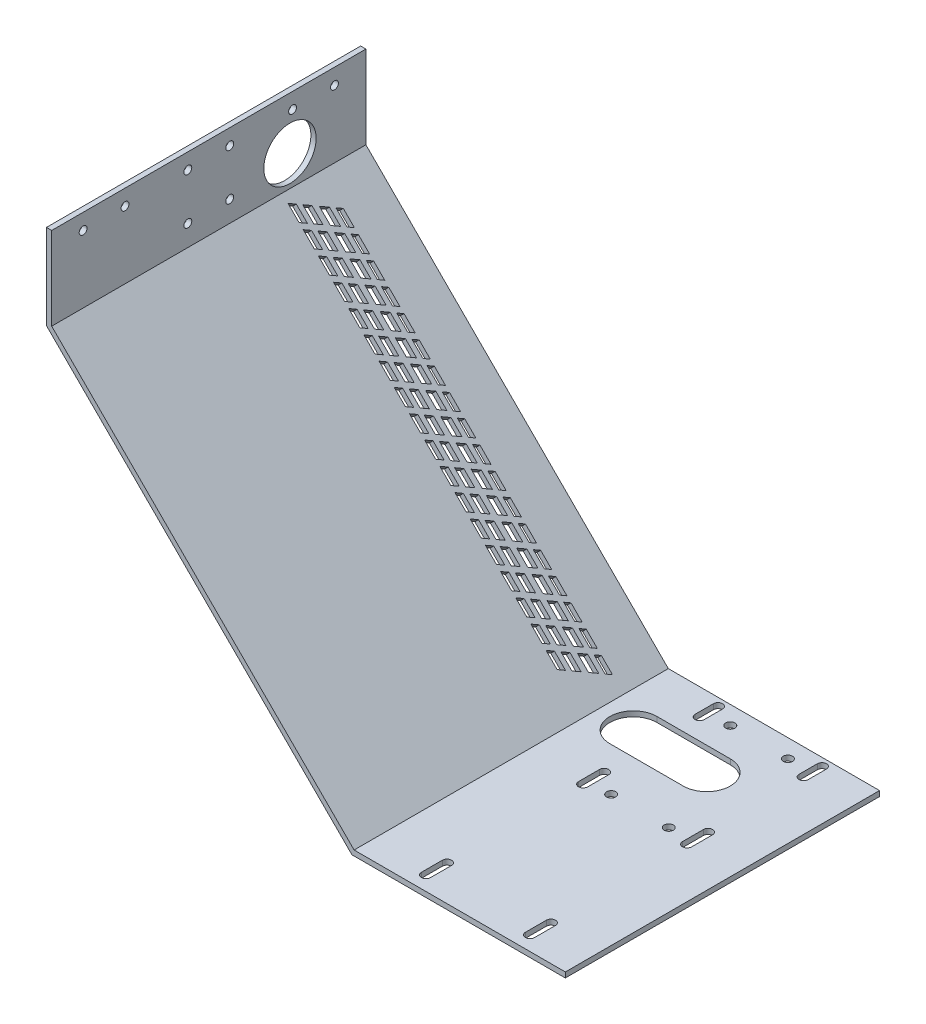
SolidWorks part; units mm, degrees
ref_plane "前视基准面" through (0, 0, 0) normal (0, 0, 1) x (1, 0, 0)
ref_plane "上视基准面" through (0, 0, 0) normal (0, 1, 0) x (1, 0, 0)
ref_plane "右视基准面" through (0, 0, 0) normal (1, 0, 0) x (0, 0, -1)
other "Configuration Table"
ref_plane "基准面1" through (0, 0, 0) normal (0, 0, -1) x (-1, 0, 0)
sketch "草图1" plane through (0, 0, 0) normal (0, 0, -1) x (-1, 0, 0)
  line L0 (199.1726, -50) -> (1, -50)
  line L1 (1, -50) -> (1, -199.1726)
  line L2 (1, -199.1726) -> (82.5, -199.1726)
  line L3 (82.5, -199.1726) -> (199.1726, -82.5)
  line L4 (199.1726, -82.5) -> (199.1726, -50)
  dimension "D1" = 81.5
  dimension "D2" = 198.1726
  dimension "D3" = 116.6726
  dimension "D4" = 149.1726
extrude "凸台-拉伸1" add sketch "草图1" against normal blind 120
sketch "草图2" plane through (0, 0, 120) normal (0, 0, 1) x (1, 0, 0)
  line L0 (-197.1726, -50) -> (-197.1726, -81.6716)
  line L1 (-197.1726, -81.6716) -> (-81.6716, -197.1726)
  line L2 (-81.6716, -197.1726) -> (-1, -197.1726)
  line L3 (-1, -197.1726) -> (-1, -50)
  line L4 (-1, -50) -> (-197.1726, -50)
  line L5 (-199.1726, -82.5) -> (-199.1726, -50) construction
  line L6 (-1, -199.1726) -> (-82.5, -199.1726) construction
  dimension "D1" = 2
  dimension "D2" = 117.501
  dimension "D3" = 198.1726
  dimension "D4" = 2
  dimension "D5" = 117.501
  dimension "D6" = 149.1726
extrude "切除-拉伸1" cut sketch "草图2" against normal through all
sketch "草图3" plane through (0, -199.1726, 0) normal (0, -1, 0) x (1, 0, 0)
  line L0 (-57.95, 106.5) -> (-57.95, 114.5)
  line L1 (-61.45, 114.5) -> (-61.45, 106.5)
  line L2 (-1, 120) -> (-1, 0) construction
  line L3 (-1, 0) -> (-82.5, 0) construction
  arc A0 (-61.45, 106.5) -> (-57.95, 106.5) centre (-59.7, 106.5) ccw
  arc A1 (-57.95, 114.5) -> (-61.45, 114.5) centre (-59.7, 114.5) ccw
  dimension "D1" = 1.75
  dimension "D2" = 58.7
  dimension "D3" = 106.5
  dimension "D4" = 114.5
extrude "切除-拉伸2" cut sketch "草图3" against normal through all
sketch "草图4" plane through (0, -199.1726, 0) normal (0, -1, 0) x (1, 0, 0)
  line L0 (-18.25, 106.5) -> (-18.25, 114.5)
  line L1 (-21.75, 114.5) -> (-21.75, 106.5)
  line L2 (-61.45, 114.5) -> (-61.45, 106.5) construction
  arc A0 (-18.25, 114.5) -> (-21.75, 114.5) centre (-20, 114.5) ccw
  arc A1 (-21.75, 106.5) -> (-18.25, 106.5) centre (-20, 106.5) ccw
  dimension "D1" = 1.75
  dimension "D2" = 41.45
  dimension "D3" = 8
extrude "切除-拉伸3" cut sketch "草图4" against normal through all
sketch "草图5" plane through (0, -199.1726, 0) normal (0, -1, 0) x (1, 0, 0)
  line L0 (-61.45, 54.5) -> (-61.45, 46.5)
  line L1 (-57.95, 46.5) -> (-57.95, 54.5)
  line L2 (-61.45, 114.5) -> (-61.45, 106.5) construction
  arc A0 (-61.45, 46.5) -> (-57.95, 46.5) centre (-59.7, 46.5) ccw
  arc A1 (-57.95, 54.5) -> (-61.45, 54.5) centre (-59.7, 54.5) ccw
  dimension "D1" = 1.75
  dimension "D2" = 1.75
  dimension "D3" = 52
  dimension "D4" = 60
extrude "切除-拉伸4" cut sketch "草图5" against normal through all
sketch "草图6" plane through (0, -199.1726, 0) normal (0, -1, 0) x (1, 0, 0)
  line L0 (-21.75, 54.5) -> (-21.75, 46.5)
  line L1 (-18.25, 46.5) -> (-18.25, 54.5)
  line L2 (-61.45, 54.5) -> (-61.45, 46.5) construction
  arc A0 (-18.25, 54.5) -> (-21.75, 54.5) centre (-20, 54.5) ccw
  arc A1 (-21.75, 46.5) -> (-18.25, 46.5) centre (-20, 46.5) ccw
  dimension "D1" = 1.75
  dimension "D2" = 41.45
  dimension "D3" = 52
  dimension "D4" = 60
extrude "切除-拉伸5" cut sketch "草图6" against normal through all
sketch "草图7" plane through (0, -199.1726, 0) normal (0, -1, 0) x (1, 0, 0)
  line L0 (-61.45, 10) -> (-61.45, 3)
  line L1 (-57.95, 3) -> (-57.95, 10)
  line L2 (-61.45, 54.5) -> (-61.45, 46.5) construction
  arc A0 (-61.45, 3) -> (-57.95, 3) centre (-59.7, 3) ccw
  arc A1 (-57.95, 10) -> (-61.45, 10) centre (-59.7, 10) ccw
  dimension "D1" = 1.75
  dimension "D2" = 1.75
  dimension "D3" = 96.5
  dimension "D4" = 103.5
extrude "切除-拉伸6" cut sketch "草图7" against normal through all
sketch "草图8" plane through (0, -199.1726, 0) normal (0, -1, 0) x (1, 0, 0)
  line L0 (-18.25, 3) -> (-18.25, 10)
  line L1 (-21.75, 10) -> (-21.75, 3)
  line L2 (-61.45, 54.5) -> (-61.45, 46.5) construction
  arc A0 (-18.25, 10) -> (-21.75, 10) centre (-20, 10) ccw
  arc A1 (-21.75, 3) -> (-18.25, 3) centre (-20, 3) ccw
  dimension "D1" = 1.75
  dimension "D2" = 41.45
  dimension "D3" = 44.5
  dimension "D4" = 51.5
extrude "切除-拉伸7" cut sketch "草图8" against normal through all
sketch "草图9" plane through (-139.4221, -139.4221, 0) normal (0.7071, 0.7071, 0) x (-0.7071, 0.7071, 0)
  line L0 (-56.4528, 25.5) -> (-55.0094, 28)
  line L1 (-55.0094, 28) -> (-61.0094, 28)
  line L2 (-61.0094, 28) -> (-62.4528, 25.5)
  line L3 (-62.4528, 25.5) -> (-56.4528, 25.5)
  line L4 (-81.6716, 0) -> (-81.6716, 120) construction
  dimension "D1" = 19.2188
  dimension "D2" = 20.6622
  dimension "D3" = 25.2188
  dimension "D4" = 26.6622
  dimension "D5" = 25.5
  dimension "D6" = 28
extrude "切除-拉伸8" cut sketch "草图9" against normal through all
sketch "草图10" plane through (-139.4221, -139.4221, 0) normal (0.7071, 0.7071, 0) x (-0.7071, 0.7071, 0)
  line L0 (-59.2056, 20.7321) -> (-57.6075, 23.5)
  line L1 (-57.6075, 23.5) -> (-63.6075, 23.5)
  line L2 (-63.6075, 23.5) -> (-65.2056, 20.7321)
  line L3 (-65.2056, 20.7321) -> (-59.2056, 20.7321)
  dimension "D1" = 2.5981
  dimension "D2" = 4.1962
  dimension "D3" = 8.5981
  dimension "D4" = 10.1962
  dimension "D5" = 2
  dimension "D6" = 4.7679
extrude "切除-拉伸9" cut sketch "草图10" against normal through all
sketch "草图11" plane through (-139.4221, -139.4221, 0) normal (0.7071, 0.7071, 0) x (-0.7071, 0.7071, 0)
  line L0 (-50.5, 32) -> (-51.8094, 29.7321)
  line L1 (-51.8094, 29.7321) -> (-45.8094, 29.7321)
  line L2 (-45.8094, 29.7321) -> (-44.5, 32)
  line L3 (-44.5, 32) -> (-50.5, 32)
  dimension "D1" = 13.3962
  dimension "D2" = 14.7056
  dimension "D3" = 19.3962
  dimension "D4" = 20.7056
  dimension "D5" = 1.7321
  dimension "D6" = 4
extrude "切除-拉伸10" cut sketch "草图11" against normal through all
sketch "草图12" plane through (-139.4221, -139.4221, 0) normal (0.7071, 0.7071, 0) x (-0.7071, 0.7071, 0)
  line L0 (-48.2528, 25.5) -> (-46.8094, 28)
  line L1 (-46.8094, 28) -> (-52.8094, 28)
  line L2 (-52.8094, 28) -> (-54.2528, 25.5)
  line L3 (-54.2528, 25.5) -> (-48.2528, 25.5)
  dimension "D1" = 2.3094
  dimension "D2" = 3.7528
  dimension "D3" = 8.3094
  dimension "D4" = 9.7528
  dimension "D5" = 4.7679
  dimension "D6" = 7.2679
extrude "切除-拉伸11" cut sketch "草图12" against normal through all
sketch "草图13" plane through (-139.4221, -139.4221, 0) normal (0.7071, 0.7071, 0) x (-0.7071, 0.7071, 0)
  line L0 (-51.0056, 20.7321) -> (-49.4075, 23.5)
  line L1 (-49.4075, 23.5) -> (-55.4075, 23.5)
  line L2 (-55.4075, 23.5) -> (-57.0056, 20.7321)
  line L3 (-57.0056, 20.7321) -> (-51.0056, 20.7321)
  dimension "D1" = 8.2
  dimension "D2" = 9.7981
  dimension "D3" = 14.2
  dimension "D4" = 15.7981
  dimension "D5" = 8.5
  dimension "D6" = 11.2679
extrude "切除-拉伸12" cut sketch "草图13" against normal through all
sketch "草图14" plane through (-139.4221, -139.4221, 0) normal (0.7071, 0.7071, 0) x (-0.7071, 0.7071, 0)
  line L0 (-42.3, 32) -> (-43.6094, 29.7321)
  line L1 (-43.6094, 29.7321) -> (-37.6094, 29.7321)
  line L2 (-37.6094, 29.7321) -> (-36.3, 32)
  line L3 (-36.3, 32) -> (-42.3, 32)
  dimension "D1" = 0.8906
  dimension "D2" = 2.2
  dimension "D3" = 6.8906
  dimension "D4" = 8.2
  dimension "D5" = 9
  dimension "D6" = 11.2679
extrude "切除-拉伸13" cut sketch "草图14" against normal through all
sketch "草图15" plane through (-139.4221, -139.4221, 0) normal (0.7071, 0.7071, 0) x (-0.7071, 0.7071, 0)
  line L0 (-40.0528, 25.5) -> (-38.6094, 28)
  line L1 (-38.6094, 28) -> (-44.6094, 28)
  line L2 (-44.6094, 28) -> (-46.0528, 25.5)
  line L3 (-46.0528, 25.5) -> (-40.0528, 25.5)
  dimension "D1" = 10.9528
  dimension "D2" = 12.3962
  dimension "D3" = 16.9528
  dimension "D4" = 18.3962
  dimension "D5" = 4
  dimension "D6" = 6.5
extrude "切除-拉伸14" cut sketch "草图15" against normal through all
sketch "草图16" plane through (-139.4221, -139.4221, 0) normal (0.7071, 0.7071, 0) x (-0.7071, 0.7071, 0)
  line L0 (-42.8056, 20.7321) -> (-41.2075, 23.5)
  line L1 (-41.2075, 23.5) -> (-47.2075, 23.5)
  line L2 (-47.2075, 23.5) -> (-48.8056, 20.7321)
  line L3 (-48.8056, 20.7321) -> (-42.8056, 20.7321)
  dimension "D1" = 4.9075
  dimension "D2" = 6.5056
  dimension "D3" = 10.9075
  dimension "D4" = 12.5056
  dimension "D5" = 2.7679
extrude "切除-拉伸15" cut sketch "草图16" against normal through all
sketch "草图17" plane through (-139.4221, -139.4221, 0) normal (0.7071, 0.7071, 0) x (-0.7071, 0.7071, 0)
  line L0 (-34.1, 32) -> (-35.4094, 29.7321)
  line L1 (-35.4094, 29.7321) -> (-29.4094, 29.7321)
  line L2 (-29.4094, 29.7321) -> (-28.1, 32)
  line L3 (-28.1, 32) -> (-34.1, 32)
  dimension "D1" = 21.5962
  dimension "D2" = 22.9056
  dimension "D3" = 27.5962
  dimension "D4" = 28.9056
  dimension "D5" = 2.2679
extrude "切除-拉伸16" cut sketch "草图17" against normal through all
sketch "草图18" plane through (-139.4221, -139.4221, 0) normal (0.7071, 0.7071, 0) x (-0.7071, 0.7071, 0)
  line L0 (-31.8528, 25.5) -> (-30.4094, 28)
  line L1 (-30.4094, 28) -> (-36.4094, 28)
  line L2 (-36.4094, 28) -> (-37.8528, 25.5)
  line L3 (-37.8528, 25.5) -> (-31.8528, 25.5)
  dimension "D1" = 2.3094
  dimension "D2" = 3.7528
  dimension "D3" = 8.3094
  dimension "D4" = 9.7528
  dimension "D5" = 4.7679
  dimension "D6" = 7.2679
extrude "切除-拉伸17" cut sketch "草图18" against normal through all
sketch "草图19" plane through (-139.4221, -139.4221, 0) normal (0.7071, 0.7071, 0) x (-0.7071, 0.7071, 0)
  line L0 (-34.6056, 20.7321) -> (-33.0075, 23.5)
  line L1 (-33.0075, 23.5) -> (-39.0075, 23.5)
  line L2 (-39.0075, 23.5) -> (-40.6056, 20.7321)
  line L3 (-40.6056, 20.7321) -> (-34.6056, 20.7321)
  dimension "D1" = 16.4
  dimension "D2" = 17.9981
  dimension "D3" = 22.4
  dimension "D4" = 23.9981
  dimension "D5" = 8.5
  dimension "D6" = 11.2679
extrude "切除-拉伸18" cut sketch "草图19" against normal through all
sketch "草图20" plane through (-139.4221, -139.4221, 0) normal (0.7071, 0.7071, 0) x (-0.7071, 0.7071, 0)
  line L0 (-25.9, 32) -> (-27.2094, 29.7321)
  line L1 (-27.2094, 29.7321) -> (-21.2094, 29.7321)
  line L2 (-21.2094, 29.7321) -> (-19.9, 32)
  line L3 (-19.9, 32) -> (-25.9, 32)
  dimension "D1" = 0.8906
  dimension "D2" = 2.2
  dimension "D3" = 6.8906
  dimension "D4" = 8.2
  dimension "D5" = 9
  dimension "D6" = 11.2679
extrude "切除-拉伸19" cut sketch "草图20" against normal through all
sketch "草图21" plane through (-139.4221, -139.4221, 0) normal (0.7071, 0.7071, 0) x (-0.7071, 0.7071, 0)
  line L0 (-23.6528, 25.5) -> (-22.2094, 28)
  line L1 (-22.2094, 28) -> (-28.2094, 28)
  line L2 (-28.2094, 28) -> (-29.6528, 25.5)
  line L3 (-29.6528, 25.5) -> (-23.6528, 25.5)
  dimension "D1" = 19.1528
  dimension "D2" = 20.5962
  dimension "D3" = 25.1528
  dimension "D4" = 26.5962
  dimension "D5" = 4
  dimension "D6" = 6.5
extrude "切除-拉伸20" cut sketch "草图21" against normal through all
sketch "草图22" plane through (-139.4221, -139.4221, 0) normal (0.7071, 0.7071, 0) x (-0.7071, 0.7071, 0)
  line L0 (-26.4056, 20.7321) -> (-24.8075, 23.5)
  line L1 (-24.8075, 23.5) -> (-30.8075, 23.5)
  line L2 (-30.8075, 23.5) -> (-32.4056, 20.7321)
  line L3 (-32.4056, 20.7321) -> (-26.4056, 20.7321)
  dimension "D1" = 4.9075
  dimension "D2" = 6.5056
  dimension "D3" = 10.9075
  dimension "D4" = 12.5056
  dimension "D5" = 2.7679
extrude "切除-拉伸21" cut sketch "草图22" against normal through all
sketch "草图23" plane through (-139.4221, -139.4221, 0) normal (0.7071, 0.7071, 0) x (-0.7071, 0.7071, 0)
  line L0 (-17.7, 32) -> (-19.0094, 29.7321)
  line L1 (-19.0094, 29.7321) -> (-13.0094, 29.7321)
  line L2 (-13.0094, 29.7321) -> (-11.7, 32)
  line L3 (-11.7, 32) -> (-17.7, 32)
  dimension "D1" = 29.7962
  dimension "D2" = 31.1056
  dimension "D3" = 35.7962
  dimension "D4" = 37.1056
  dimension "D5" = 2.2679
extrude "切除-拉伸22" cut sketch "草图23" against normal through all
sketch "草图24" plane through (-139.4221, -139.4221, 0) normal (0.7071, 0.7071, 0) x (-0.7071, 0.7071, 0)
  line L0 (-15.4528, 25.5) -> (-14.0094, 28)
  line L1 (-14.0094, 28) -> (-20.0094, 28)
  line L2 (-20.0094, 28) -> (-21.4528, 25.5)
  line L3 (-21.4528, 25.5) -> (-15.4528, 25.5)
  dimension "D1" = 2.3094
  dimension "D2" = 3.7528
  dimension "D3" = 8.3094
  dimension "D4" = 9.7528
  dimension "D5" = 4.7679
  dimension "D6" = 7.2679
extrude "切除-拉伸23" cut sketch "草图24" against normal through all
sketch "草图25" plane through (-139.4221, -139.4221, 0) normal (0.7071, 0.7071, 0) x (-0.7071, 0.7071, 0)
  line L0 (-18.2056, 20.7321) -> (-16.6075, 23.5)
  line L1 (-16.6075, 23.5) -> (-22.6075, 23.5)
  line L2 (-22.6075, 23.5) -> (-24.2056, 20.7321)
  line L3 (-24.2056, 20.7321) -> (-18.2056, 20.7321)
  dimension "D1" = 24.6
  dimension "D2" = 26.1981
  dimension "D3" = 30.6
  dimension "D4" = 32.1981
  dimension "D5" = 8.5
  dimension "D6" = 11.2679
extrude "切除-拉伸24" cut sketch "草图25" against normal through all
sketch "草图26" plane through (-139.4221, -139.4221, 0) normal (0.7071, 0.7071, 0) x (-0.7071, 0.7071, 0)
  line L0 (-9.5, 32) -> (-10.8094, 29.7321)
  line L1 (-10.8094, 29.7321) -> (-4.8094, 29.7321)
  line L2 (-4.8094, 29.7321) -> (-3.5, 32)
  line L3 (-3.5, 32) -> (-9.5, 32)
  dimension "D1" = 0.8906
  dimension "D2" = 2.2
  dimension "D3" = 6.8906
  dimension "D4" = 8.2
  dimension "D5" = 9
  dimension "D6" = 11.2679
extrude "切除-拉伸25" cut sketch "草图26" against normal through all
sketch "草图27" plane through (-139.4221, -139.4221, 0) normal (0.7071, 0.7071, 0) x (-0.7071, 0.7071, 0)
  line L0 (-7.2528, 25.5) -> (-5.8094, 28)
  line L1 (-5.8094, 28) -> (-11.8094, 28)
  line L2 (-11.8094, 28) -> (-13.2528, 25.5)
  line L3 (-13.2528, 25.5) -> (-7.2528, 25.5)
  dimension "D1" = 27.3528
  dimension "D2" = 28.7962
  dimension "D3" = 33.3528
  dimension "D4" = 34.7962
  dimension "D5" = 4
  dimension "D6" = 6.5
extrude "切除-拉伸26" cut sketch "草图27" against normal through all
sketch "草图28" plane through (-139.4221, -139.4221, 0) normal (0.7071, 0.7071, 0) x (-0.7071, 0.7071, 0)
  line L0 (-10.0056, 20.7321) -> (-8.4075, 23.5)
  line L1 (-8.4075, 23.5) -> (-14.4075, 23.5)
  line L2 (-14.4075, 23.5) -> (-16.0056, 20.7321)
  line L3 (-16.0056, 20.7321) -> (-10.0056, 20.7321)
  dimension "D1" = 4.9075
  dimension "D2" = 6.5056
  dimension "D3" = 10.9075
  dimension "D4" = 12.5056
  dimension "D5" = 2.7679
extrude "切除-拉伸27" cut sketch "草图28" against normal through all
sketch "草图29" plane through (-139.4221, -139.4221, 0) normal (0.7071, 0.7071, 0) x (-0.7071, 0.7071, 0)
  line L0 (-1.3, 32) -> (-2.6094, 29.7321)
  line L1 (-2.6094, 29.7321) -> (3.3906, 29.7321)
  line L2 (3.3906, 29.7321) -> (4.7, 32)
  line L3 (4.7, 32) -> (-1.3, 32)
  dimension "D1" = 37.9962
  dimension "D2" = 39.3056
  dimension "D3" = 43.9962
  dimension "D4" = 45.3056
  dimension "D5" = 2.2679
extrude "切除-拉伸28" cut sketch "草图29" against normal through all
sketch "草图30" plane through (-139.4221, -139.4221, 0) normal (0.7071, 0.7071, 0) x (-0.7071, 0.7071, 0)
  line L0 (0.9472, 25.5) -> (2.3906, 28)
  line L1 (2.3906, 28) -> (-3.6094, 28)
  line L2 (-3.6094, 28) -> (-5.0528, 25.5)
  line L3 (-5.0528, 25.5) -> (0.9472, 25.5)
  dimension "D1" = 2.3094
  dimension "D2" = 3.7528
  dimension "D3" = 8.3094
  dimension "D4" = 9.7528
  dimension "D5" = 4.7679
  dimension "D6" = 7.2679
extrude "切除-拉伸29" cut sketch "草图30" against normal through all
sketch "草图31" plane through (-139.4221, -139.4221, 0) normal (0.7071, 0.7071, 0) x (-0.7071, 0.7071, 0)
  line L0 (-1.8056, 20.7321) -> (-0.2075, 23.5)
  line L1 (-0.2075, 23.5) -> (-6.2075, 23.5)
  line L2 (-6.2075, 23.5) -> (-7.8056, 20.7321)
  line L3 (-7.8056, 20.7321) -> (-1.8056, 20.7321)
  dimension "D1" = 32.8
  dimension "D2" = 34.3981
  dimension "D3" = 38.8
  dimension "D4" = 40.3981
  dimension "D5" = 8.5
  dimension "D6" = 11.2679
extrude "切除-拉伸30" cut sketch "草图31" against normal through all
sketch "草图32" plane through (-139.4221, -139.4221, 0) normal (0.7071, 0.7071, 0) x (-0.7071, 0.7071, 0)
  line L0 (6.9, 32) -> (5.5906, 29.7321)
  line L1 (5.5906, 29.7321) -> (11.5906, 29.7321)
  line L2 (11.5906, 29.7321) -> (12.9, 32)
  line L3 (12.9, 32) -> (6.9, 32)
  dimension "D1" = 0.8906
  dimension "D2" = 2.2
  dimension "D3" = 6.8906
  dimension "D4" = 8.2
  dimension "D5" = 9
  dimension "D6" = 11.2679
extrude "切除-拉伸31" cut sketch "草图32" against normal through all
sketch "草图33" plane through (-139.4221, -139.4221, 0) normal (0.7071, 0.7071, 0) x (-0.7071, 0.7071, 0)
  line L0 (9.1472, 25.5) -> (10.5906, 28)
  line L1 (10.5906, 28) -> (4.5906, 28)
  line L2 (4.5906, 28) -> (3.1472, 25.5)
  line L3 (3.1472, 25.5) -> (9.1472, 25.5)
  dimension "D1" = 35.5528
  dimension "D2" = 36.9962
  dimension "D3" = 41.5528
  dimension "D4" = 42.9962
  dimension "D5" = 4
  dimension "D6" = 6.5
extrude "切除-拉伸32" cut sketch "草图33" against normal through all
sketch "草图34" plane through (-139.4221, -139.4221, 0) normal (0.7071, 0.7071, 0) x (-0.7071, 0.7071, 0)
  line L0 (6.3944, 20.7321) -> (7.9925, 23.5)
  line L1 (7.9925, 23.5) -> (1.9925, 23.5)
  line L2 (1.9925, 23.5) -> (0.3944, 20.7321)
  line L3 (0.3944, 20.7321) -> (6.3944, 20.7321)
  dimension "D1" = 4.9075
  dimension "D2" = 6.5056
  dimension "D3" = 10.9075
  dimension "D4" = 12.5056
  dimension "D5" = 2.7679
extrude "切除-拉伸33" cut sketch "草图34" against normal through all
sketch "草图35" plane through (-139.4221, -139.4221, 0) normal (0.7071, 0.7071, 0) x (-0.7071, 0.7071, 0)
  line L0 (15.1, 32) -> (13.7906, 29.7321)
  line L1 (13.7906, 29.7321) -> (19.7906, 29.7321)
  line L2 (19.7906, 29.7321) -> (21.1, 32)
  line L3 (21.1, 32) -> (15.1, 32)
  dimension "D1" = 46.1962
  dimension "D2" = 47.5056
  dimension "D3" = 52.1962
  dimension "D4" = 53.5056
  dimension "D5" = 2.2679
extrude "切除-拉伸34" cut sketch "草图35" against normal through all
sketch "草图36" plane through (-139.4221, -139.4221, 0) normal (0.7071, 0.7071, 0) x (-0.7071, 0.7071, 0)
  line L0 (17.3472, 25.5) -> (18.7906, 28)
  line L1 (18.7906, 28) -> (12.7906, 28)
  line L2 (12.7906, 28) -> (11.3472, 25.5)
  line L3 (11.3472, 25.5) -> (17.3472, 25.5)
  dimension "D1" = 2.3094
  dimension "D2" = 3.7528
  dimension "D3" = 8.3094
  dimension "D4" = 9.7528
  dimension "D5" = 4.7679
  dimension "D6" = 7.2679
extrude "切除-拉伸35" cut sketch "草图36" against normal through all
sketch "草图37" plane through (-139.4221, -139.4221, 0) normal (0.7071, 0.7071, 0) x (-0.7071, 0.7071, 0)
  line L0 (14.5944, 20.7321) -> (16.1925, 23.5)
  line L1 (16.1925, 23.5) -> (10.1925, 23.5)
  line L2 (10.1925, 23.5) -> (8.5944, 20.7321)
  line L3 (8.5944, 20.7321) -> (14.5944, 20.7321)
  dimension "D1" = 41
  dimension "D2" = 42.5981
  dimension "D3" = 47
  dimension "D4" = 48.5981
  dimension "D5" = 8.5
  dimension "D6" = 11.2679
extrude "切除-拉伸36" cut sketch "草图37" against normal through all
sketch "草图38" plane through (-139.4221, -139.4221, 0) normal (0.7071, 0.7071, 0) x (-0.7071, 0.7071, 0)
  line L0 (23.3, 32) -> (21.9906, 29.7321)
  line L1 (21.9906, 29.7321) -> (27.9906, 29.7321)
  line L2 (27.9906, 29.7321) -> (29.3, 32)
  line L3 (29.3, 32) -> (23.3, 32)
  dimension "D1" = 0.8906
  dimension "D2" = 2.2
  dimension "D3" = 6.8906
  dimension "D4" = 8.2
  dimension "D5" = 9
  dimension "D6" = 11.2679
extrude "切除-拉伸37" cut sketch "草图38" against normal through all
sketch "草图39" plane through (-139.4221, -139.4221, 0) normal (0.7071, 0.7071, 0) x (-0.7071, 0.7071, 0)
  line L0 (25.5472, 25.5) -> (26.9906, 28)
  line L1 (26.9906, 28) -> (20.9906, 28)
  line L2 (20.9906, 28) -> (19.5472, 25.5)
  line L3 (19.5472, 25.5) -> (25.5472, 25.5)
  dimension "D1" = 43.7528
  dimension "D2" = 45.1962
  dimension "D3" = 49.7528
  dimension "D4" = 51.1962
  dimension "D5" = 4
  dimension "D6" = 6.5
extrude "切除-拉伸38" cut sketch "草图39" against normal through all
sketch "草图40" plane through (-139.4221, -139.4221, 0) normal (0.7071, 0.7071, 0) x (-0.7071, 0.7071, 0)
  line L0 (22.7944, 20.7321) -> (24.3925, 23.5)
  line L1 (24.3925, 23.5) -> (18.3925, 23.5)
  line L2 (18.3925, 23.5) -> (16.7944, 20.7321)
  line L3 (16.7944, 20.7321) -> (22.7944, 20.7321)
  dimension "D1" = 4.9075
  dimension "D2" = 6.5056
  dimension "D3" = 10.9075
  dimension "D4" = 12.5056
  dimension "D5" = 2.7679
extrude "切除-拉伸39" cut sketch "草图40" against normal through all
sketch "草图41" plane through (-139.4221, -139.4221, 0) normal (0.7071, 0.7071, 0) x (-0.7071, 0.7071, 0)
  line L0 (31.5, 32) -> (30.1906, 29.7321)
  line L1 (30.1906, 29.7321) -> (36.1906, 29.7321)
  line L2 (36.1906, 29.7321) -> (37.5, 32)
  line L3 (37.5, 32) -> (31.5, 32)
  dimension "D1" = 54.3962
  dimension "D2" = 55.7056
  dimension "D3" = 60.3962
  dimension "D4" = 61.7056
  dimension "D5" = 2.2679
extrude "切除-拉伸40" cut sketch "草图41" against normal through all
sketch "草图42" plane through (-139.4221, -139.4221, 0) normal (0.7071, 0.7071, 0) x (-0.7071, 0.7071, 0)
  line L0 (33.7472, 25.5) -> (35.1906, 28)
  line L1 (35.1906, 28) -> (29.1906, 28)
  line L2 (29.1906, 28) -> (27.7472, 25.5)
  line L3 (27.7472, 25.5) -> (33.7472, 25.5)
  dimension "D1" = 2.3094
  dimension "D2" = 3.7528
  dimension "D3" = 8.3094
  dimension "D4" = 9.7528
  dimension "D5" = 4.7679
  dimension "D6" = 7.2679
extrude "切除-拉伸41" cut sketch "草图42" against normal through all
sketch "草图43" plane through (-139.4221, -139.4221, 0) normal (0.7071, 0.7071, 0) x (-0.7071, 0.7071, 0)
  line L0 (30.9944, 20.7321) -> (32.5925, 23.5)
  line L1 (32.5925, 23.5) -> (26.5925, 23.5)
  line L2 (26.5925, 23.5) -> (24.9944, 20.7321)
  line L3 (24.9944, 20.7321) -> (30.9944, 20.7321)
  dimension "D1" = 49.2
  dimension "D2" = 50.7981
  dimension "D3" = 55.2
  dimension "D4" = 56.7981
  dimension "D5" = 8.5
  dimension "D6" = 11.2679
extrude "切除-拉伸42" cut sketch "草图43" against normal through all
sketch "草图44" plane through (-139.4221, -139.4221, 0) normal (0.7071, 0.7071, 0) x (-0.7071, 0.7071, 0)
  line L0 (39.7, 32) -> (38.3906, 29.7321)
  line L1 (38.3906, 29.7321) -> (44.3906, 29.7321)
  line L2 (44.3906, 29.7321) -> (45.7, 32)
  line L3 (45.7, 32) -> (39.7, 32)
  dimension "D1" = 0.8906
  dimension "D2" = 2.2
  dimension "D3" = 6.8906
  dimension "D4" = 8.2
  dimension "D5" = 9
  dimension "D6" = 11.2679
extrude "切除-拉伸43" cut sketch "草图44" against normal through all
sketch "草图45" plane through (-139.4221, -139.4221, 0) normal (0.7071, 0.7071, 0) x (-0.7071, 0.7071, 0)
  line L0 (41.9472, 25.5) -> (43.3906, 28)
  line L1 (43.3906, 28) -> (37.3906, 28)
  line L2 (37.3906, 28) -> (35.9472, 25.5)
  line L3 (35.9472, 25.5) -> (41.9472, 25.5)
  dimension "D1" = 51.9528
  dimension "D2" = 53.3962
  dimension "D3" = 57.9528
  dimension "D4" = 59.3962
  dimension "D5" = 4
  dimension "D6" = 6.5
extrude "切除-拉伸44" cut sketch "草图45" against normal through all
sketch "草图46" plane through (-139.4221, -139.4221, 0) normal (0.7071, 0.7071, 0) x (-0.7071, 0.7071, 0)
  line L0 (39.1944, 20.7321) -> (40.7925, 23.5)
  line L1 (40.7925, 23.5) -> (34.7925, 23.5)
  line L2 (34.7925, 23.5) -> (33.1944, 20.7321)
  line L3 (33.1944, 20.7321) -> (39.1944, 20.7321)
  dimension "D1" = 4.9075
  dimension "D2" = 6.5056
  dimension "D3" = 10.9075
  dimension "D4" = 12.5056
  dimension "D5" = 2.7679
extrude "切除-拉伸45" cut sketch "草图46" against normal through all
sketch "草图47" plane through (-139.4221, -139.4221, 0) normal (0.7071, 0.7071, 0) x (-0.7071, 0.7071, 0)
  line L0 (47.9, 32) -> (46.5906, 29.7321)
  line L1 (46.5906, 29.7321) -> (52.5906, 29.7321)
  line L2 (52.5906, 29.7321) -> (53.9, 32)
  line L3 (53.9, 32) -> (47.9, 32)
  dimension "D1" = 62.5962
  dimension "D2" = 63.9056
  dimension "D3" = 68.5962
  dimension "D4" = 69.9056
  dimension "D5" = 2.2679
extrude "切除-拉伸46" cut sketch "草图47" against normal through all
sketch "草图48" plane through (-139.4221, -139.4221, 0) normal (0.7071, 0.7071, 0) x (-0.7071, 0.7071, 0)
  line L0 (50.1472, 25.5) -> (51.5906, 28)
  line L1 (51.5906, 28) -> (45.5906, 28)
  line L2 (45.5906, 28) -> (44.1472, 25.5)
  line L3 (44.1472, 25.5) -> (50.1472, 25.5)
  dimension "D1" = 2.3094
  dimension "D2" = 3.7528
  dimension "D3" = 8.3094
  dimension "D4" = 9.7528
  dimension "D5" = 4.7679
  dimension "D6" = 7.2679
extrude "切除-拉伸47" cut sketch "草图48" against normal through all
sketch "草图49" plane through (-139.4221, -139.4221, 0) normal (0.7071, 0.7071, 0) x (-0.7071, 0.7071, 0)
  line L0 (47.3944, 20.7321) -> (48.9925, 23.5)
  line L1 (48.9925, 23.5) -> (42.9925, 23.5)
  line L2 (42.9925, 23.5) -> (41.3944, 20.7321)
  line L3 (41.3944, 20.7321) -> (47.3944, 20.7321)
  dimension "D1" = 57.4
  dimension "D2" = 58.9981
  dimension "D3" = 63.4
  dimension "D4" = 64.9981
  dimension "D5" = 8.5
  dimension "D6" = 11.2679
extrude "切除-拉伸48" cut sketch "草图49" against normal through all
sketch "草图50" plane through (-139.4221, -139.4221, 0) normal (0.7071, 0.7071, 0) x (-0.7071, 0.7071, 0)
  line L0 (56.1, 32) -> (54.7906, 29.7321)
  line L1 (54.7906, 29.7321) -> (60.7906, 29.7321)
  line L2 (60.7906, 29.7321) -> (62.1, 32)
  line L3 (62.1, 32) -> (56.1, 32)
  dimension "D1" = 0.8906
  dimension "D2" = 2.2
  dimension "D3" = 6.8906
  dimension "D4" = 8.2
  dimension "D5" = 9
  dimension "D6" = 11.2679
extrude "切除-拉伸49" cut sketch "草图50" against normal through all
sketch "草图51" plane through (-139.4221, -139.4221, 0) normal (0.7071, 0.7071, 0) x (-0.7071, 0.7071, 0)
  line L0 (58.3472, 25.5) -> (59.7906, 28)
  line L1 (59.7906, 28) -> (53.7906, 28)
  line L2 (53.7906, 28) -> (52.3472, 25.5)
  line L3 (52.3472, 25.5) -> (58.3472, 25.5)
  dimension "D1" = 60.1528
  dimension "D2" = 61.5962
  dimension "D3" = 66.1528
  dimension "D4" = 67.5962
  dimension "D5" = 4
  dimension "D6" = 6.5
extrude "切除-拉伸50" cut sketch "草图51" against normal through all
sketch "草图52" plane through (-139.4221, -139.4221, 0) normal (0.7071, 0.7071, 0) x (-0.7071, 0.7071, 0)
  line L0 (55.5944, 20.7321) -> (57.1925, 23.5)
  line L1 (57.1925, 23.5) -> (51.1925, 23.5)
  line L2 (51.1925, 23.5) -> (49.5944, 20.7321)
  line L3 (49.5944, 20.7321) -> (55.5944, 20.7321)
  dimension "D1" = 4.9075
  dimension "D2" = 6.5056
  dimension "D3" = 10.9075
  dimension "D4" = 12.5056
  dimension "D5" = 2.7679
extrude "切除-拉伸51" cut sketch "草图52" against normal through all
sketch "草图53" plane through (-139.4221, -139.4221, 0) normal (0.7071, 0.7071, 0) x (-0.7071, 0.7071, 0)
  line L0 (-69.5603, 17) -> (-68.4056, 19)
  line L1 (-68.4056, 19) -> (-74.4056, 19)
  line L2 (-74.4056, 19) -> (-75.5603, 17)
  line L3 (-75.5603, 17) -> (-69.5603, 17)
  dimension "D1" = 60.6
  dimension "D2" = 61.7547
  dimension "D3" = 66.6
  dimension "D4" = 67.7547
  dimension "D5" = 13
  dimension "D6" = 15
extrude "切除-拉伸52" cut sketch "草图53" against normal through all
sketch "草图54" plane through (-139.4221, -139.4221, 0) normal (0.7071, 0.7071, 0) x (-0.7071, 0.7071, 0)
  line L0 (64.3, 32) -> (62.9906, 29.7321)
  line L1 (62.9906, 29.7321) -> (68.9906, 29.7321)
  line L2 (68.9906, 29.7321) -> (70.3, 32)
  line L3 (70.3, 32) -> (64.3, 32)
  dimension "D1" = 0.8906
  dimension "D2" = 2.2
  dimension "D3" = 6.8906
  dimension "D4" = 8.2
  dimension "D5" = 12.7321
  dimension "D6" = 15
extrude "切除-拉伸53" cut sketch "草图54" against normal through all
sketch "草图55" plane through (-139.4221, -139.4221, 0) normal (0.7071, 0.7071, 0) x (-0.7071, 0.7071, 0)
  line L0 (66.5472, 25.5) -> (67.9906, 28)
  line L1 (67.9906, 28) -> (61.9906, 28)
  line L2 (61.9906, 28) -> (60.5472, 25.5)
  line L3 (60.5472, 25.5) -> (66.5472, 25.5)
  dimension "D1" = 136.1075
  dimension "D2" = 137.5509
  dimension "D3" = 142.1075
  dimension "D4" = 143.5509
  dimension "D5" = 4
  dimension "D6" = 6.5
extrude "切除-拉伸54" cut sketch "草图55" against normal through all
sketch "草图56" plane through (-139.4221, -139.4221, 0) normal (0.7071, 0.7071, 0) x (-0.7071, 0.7071, 0)
  line L0 (63.7944, 20.7321) -> (65.3925, 23.5)
  line L1 (65.3925, 23.5) -> (59.3925, 23.5)
  line L2 (59.3925, 23.5) -> (57.7944, 20.7321)
  line L3 (57.7944, 20.7321) -> (63.7944, 20.7321)
  dimension "D1" = 4.9075
  dimension "D2" = 6.5056
  dimension "D3" = 10.9075
  dimension "D4" = 12.5056
  dimension "D5" = 3.7321
  dimension "D6" = 6.5
extrude "切除-拉伸55" cut sketch "草图56" against normal through all
sketch "草图57" plane through (-139.4221, -139.4221, 0) normal (0.7071, 0.7071, 0) x (-0.7071, 0.7071, 0)
  line L0 (-71.8075, 23.5) -> (-73.4056, 20.7321)
  line L1 (-73.4056, 20.7321) -> (-67.4056, 20.7321)
  line L2 (-67.4056, 20.7321) -> (-65.8075, 23.5)
  line L3 (-65.8075, 23.5) -> (-71.8075, 23.5)
  dimension "D1" = 2.1547
  dimension "D2" = 3.7528
  dimension "D3" = 8.1547
  dimension "D4" = 9.7528
  dimension "D5" = 8.5
  dimension "D6" = 11.2679
extrude "切除-拉伸56" cut sketch "草图57" against normal through all
sketch "草图58" plane through (-139.4221, -139.4221, 0) normal (0.7071, 0.7071, 0) x (-0.7071, 0.7071, 0)
  line L0 (-69.2094, 28) -> (-70.6528, 25.5)
  line L1 (-70.6528, 25.5) -> (-64.6528, 25.5)
  line L2 (-64.6528, 25.5) -> (-63.2094, 28)
  line L3 (-63.2094, 28) -> (-69.2094, 28)
  dimension "D1" = 133.5094
  dimension "D2" = 134.9528
  dimension "D3" = 139.5094
  dimension "D4" = 140.9528
  dimension "D5" = 8.5
  dimension "D6" = 11
extrude "切除-拉伸57" cut sketch "草图58" against normal through all
sketch "草图59" plane through (-139.4221, -139.4221, 0) normal (0.7071, 0.7071, 0) x (-0.7071, 0.7071, 0)
  line L0 (67.5925, 23.5) -> (65.9944, 20.7321)
  line L1 (65.9944, 20.7321) -> (71.9944, 20.7321)
  line L2 (71.9944, 20.7321) -> (73.5925, 23.5)
  line L3 (73.5925, 23.5) -> (67.5925, 23.5)
  dimension "D1" = 141.5547
  dimension "D2" = 143.1528
  dimension "D3" = 147.5547
  dimension "D4" = 149.1528
  dimension "D5" = 8.5
  dimension "D6" = 11.2679
extrude "切除-拉伸58" cut sketch "草图59" against normal through all
sketch "草图60" plane through (-139.4221, -139.4221, 0) normal (0.7071, 0.7071, 0) x (-0.7071, 0.7071, 0)
  line L0 (70.1906, 28) -> (68.7472, 25.5)
  line L1 (68.7472, 25.5) -> (74.7472, 25.5)
  line L2 (74.7472, 25.5) -> (76.1906, 28)
  line L3 (76.1906, 28) -> (70.1906, 28)
  dimension "D1" = 1.1547
  dimension "D2" = 2.5981
  dimension "D3" = 3.4019
  dimension "D4" = 4.8453
  dimension "D5" = 8.5
  dimension "D6" = 11
extrude "切除-拉伸59" cut sketch "草图60" against normal through all
sketch "草图61" plane through (-139.4221, -139.4221, 0) normal (0.7071, 0.7071, 0) x (-0.7071, 0.7071, 0)
  line L0 (72.5, 32) -> (71.1906, 29.7321)
  line L1 (71.1906, 29.7321) -> (77.1906, 29.7321)
  line L2 (77.1906, 29.7321) -> (78.5, 32)
  line L3 (78.5, 32) -> (72.5, 32)
  dimension "D1" = 146.7509
  dimension "D2" = 148.0603
  dimension "D3" = 152.7509
  dimension "D4" = 154.0603
  dimension "D5" = 1.7321
  dimension "D6" = 4
extrude "切除-拉伸60" cut sketch "草图61" against normal through all
sketch "草图62" plane through (-139.4221, -139.4221, 0) normal (0.7071, 0.7071, 0) x (-0.7071, 0.7071, 0)
  line L0 (-58.7, 32) -> (-60.0094, 29.7321)
  line L1 (-60.0094, 29.7321) -> (-54.0094, 29.7321)
  line L2 (-54.0094, 29.7321) -> (-52.7, 32)
  line L3 (-52.7, 32) -> (-58.7, 32)
  dimension "D1" = 131.2
  dimension "D2" = 132.5094
  dimension "D3" = 137.2
  dimension "D4" = 138.5094
  dimension "D5" = 12.7321
  dimension "D6" = 15
extrude "切除-拉伸61" cut sketch "草图62" against normal through all
sketch "草图63" plane through (-139.4221, -139.4221, 0) normal (0.7071, 0.7071, 0) x (-0.7071, 0.7071, 0)
  line L0 (69.8397, 17) -> (70.9944, 19)
  line L1 (70.9944, 19) -> (64.9944, 19)
  line L2 (64.9944, 19) -> (63.8397, 17)
  line L3 (63.8397, 17) -> (69.8397, 17)
  dimension "D1" = 139.4
  dimension "D2" = 140.5547
  dimension "D3" = 145.4
  dimension "D4" = 146.5547
  dimension "D5" = 13
  dimension "D6" = 15
extrude "切除-拉伸62" cut sketch "草图63" against normal through all
sketch "草图64" plane through (-139.4221, -139.4221, 0) normal (0.7071, 0.7071, 0) x (-0.7071, 0.7071, 0)
  line L0 (-66.9, 32) -> (-68.2094, 29.7321)
  line L1 (-68.2094, 29.7321) -> (-62.2094, 29.7321)
  line L2 (-62.2094, 29.7321) -> (-60.9, 32)
  line L3 (-60.9, 32) -> (-66.9, 32)
  dimension "D1" = 139.4
  dimension "D2" = 140.7094
  dimension "D3" = 145.4
  dimension "D4" = 146.7094
  dimension "D5" = 12.7321
  dimension "D6" = 15
extrude "切除-拉伸63" cut sketch "草图64" against normal through all
sketch "草图65" plane through (-139.4221, -139.4221, 0) normal (0.7071, 0.7071, 0) x (-0.7071, 0.7071, 0)
  line L0 (61.6397, 17) -> (62.7944, 19)
  line L1 (62.7944, 19) -> (56.7944, 19)
  line L2 (56.7944, 19) -> (55.6397, 17)
  line L3 (55.6397, 17) -> (61.6397, 17)
  dimension "D1" = 131.2
  dimension "D2" = 132.3547
  dimension "D3" = 137.2
  dimension "D4" = 138.3547
  dimension "D5" = 13
  dimension "D6" = 15
extrude "切除-拉伸64" cut sketch "草图65" against normal through all
sketch "草图66" plane through (-139.4221, -139.4221, 0) normal (0.7071, 0.7071, 0) x (-0.7071, 0.7071, 0)
  line L0 (53.4397, 17) -> (54.5944, 19)
  line L1 (54.5944, 19) -> (48.5944, 19)
  line L2 (48.5944, 19) -> (47.4397, 17)
  line L3 (47.4397, 17) -> (53.4397, 17)
  dimension "D1" = 23.9056
  dimension "D2" = 25.0603
  dimension "D3" = 29.9056
  dimension "D4" = 31.0603
  dimension "D5" = 2
extrude "切除-拉伸65" cut sketch "草图66" against normal through all
sketch "草图67" plane through (-139.4221, -139.4221, 0) normal (0.7071, 0.7071, 0) x (-0.7071, 0.7071, 0)
  line L0 (45.2397, 17) -> (46.3944, 19)
  line L1 (46.3944, 19) -> (40.3944, 19)
  line L2 (40.3944, 19) -> (39.2397, 17)
  line L3 (39.2397, 17) -> (45.2397, 17)
  dimension "D1" = 114.8
  dimension "D2" = 115.9547
  dimension "D3" = 120.8
  dimension "D4" = 121.9547
  dimension "D5" = 13
  dimension "D6" = 15
extrude "切除-拉伸66" cut sketch "草图67" against normal through all
sketch "草图68" plane through (-139.4221, -139.4221, 0) normal (0.7071, 0.7071, 0) x (-0.7071, 0.7071, 0)
  line L0 (37.0397, 17) -> (38.1944, 19)
  line L1 (38.1944, 19) -> (32.1944, 19)
  line L2 (32.1944, 19) -> (31.0397, 17)
  line L3 (31.0397, 17) -> (37.0397, 17)
  dimension "D1" = 40.3056
  dimension "D2" = 41.4603
  dimension "D3" = 46.3056
  dimension "D4" = 47.4603
  dimension "D5" = 2
extrude "切除-拉伸67" cut sketch "草图68" against normal through all
sketch "草图69" plane through (-139.4221, -139.4221, 0) normal (0.7071, 0.7071, 0) x (-0.7071, 0.7071, 0)
  line L0 (28.8397, 17) -> (29.9944, 19)
  line L1 (29.9944, 19) -> (23.9944, 19)
  line L2 (23.9944, 19) -> (22.8397, 17)
  line L3 (22.8397, 17) -> (28.8397, 17)
  dimension "D1" = 98.4
  dimension "D2" = 99.5547
  dimension "D3" = 104.4
  dimension "D4" = 105.5547
  dimension "D5" = 13
  dimension "D6" = 15
extrude "切除-拉伸68" cut sketch "草图69" against normal through all
sketch "草图70" plane through (-139.4221, -139.4221, 0) normal (0.7071, 0.7071, 0) x (-0.7071, 0.7071, 0)
  line L0 (20.6397, 17) -> (21.7944, 19)
  line L1 (21.7944, 19) -> (15.7944, 19)
  line L2 (15.7944, 19) -> (14.6397, 17)
  line L3 (14.6397, 17) -> (20.6397, 17)
  dimension "D1" = 56.7056
  dimension "D2" = 57.8603
  dimension "D3" = 62.7056
  dimension "D4" = 63.8603
  dimension "D5" = 2
extrude "切除-拉伸69" cut sketch "草图70" against normal through all
sketch "草图71" plane through (-139.4221, -139.4221, 0) normal (0.7071, 0.7071, 0) x (-0.7071, 0.7071, 0)
  line L0 (12.4397, 17) -> (13.5944, 19)
  line L1 (13.5944, 19) -> (7.5944, 19)
  line L2 (7.5944, 19) -> (6.4397, 17)
  line L3 (6.4397, 17) -> (12.4397, 17)
  dimension "D1" = 82
  dimension "D2" = 83.1547
  dimension "D3" = 88
  dimension "D4" = 89.1547
  dimension "D5" = 13
  dimension "D6" = 15
extrude "切除-拉伸70" cut sketch "草图71" against normal through all
sketch "草图72" plane through (-139.4221, -139.4221, 0) normal (0.7071, 0.7071, 0) x (-0.7071, 0.7071, 0)
  line L0 (4.2397, 17) -> (5.3944, 19)
  line L1 (5.3944, 19) -> (-0.6056, 19)
  line L2 (-0.6056, 19) -> (-1.7603, 17)
  line L3 (-1.7603, 17) -> (4.2397, 17)
  dimension "D1" = 73.1056
  dimension "D2" = 74.2603
  dimension "D3" = 79.1056
  dimension "D4" = 80.2603
  dimension "D5" = 2
extrude "切除-拉伸71" cut sketch "草图72" against normal through all
sketch "草图73" plane through (-139.4221, -139.4221, 0) normal (0.7071, 0.7071, 0) x (-0.7071, 0.7071, 0)
  line L0 (-3.9603, 17) -> (-2.8056, 19)
  line L1 (-2.8056, 19) -> (-8.8056, 19)
  line L2 (-8.8056, 19) -> (-9.9603, 17)
  line L3 (-9.9603, 17) -> (-3.9603, 17)
  dimension "D1" = 65.6
  dimension "D2" = 66.7547
  dimension "D3" = 71.6
  dimension "D4" = 72.7547
  dimension "D5" = 13
  dimension "D6" = 15
extrude "切除-拉伸72" cut sketch "草图73" against normal through all
sketch "草图74" plane through (-139.4221, -139.4221, 0) normal (0.7071, 0.7071, 0) x (-0.7071, 0.7071, 0)
  line L0 (-12.1603, 17) -> (-11.0056, 19)
  line L1 (-11.0056, 19) -> (-17.0056, 19)
  line L2 (-17.0056, 19) -> (-18.1603, 17)
  line L3 (-18.1603, 17) -> (-12.1603, 17)
  dimension "D1" = 89.5056
  dimension "D2" = 90.6603
  dimension "D3" = 95.5056
  dimension "D4" = 96.6603
  dimension "D5" = 2
extrude "切除-拉伸73" cut sketch "草图74" against normal through all
sketch "草图75" plane through (-139.4221, -139.4221, 0) normal (0.7071, 0.7071, 0) x (-0.7071, 0.7071, 0)
  line L0 (-20.3603, 17) -> (-19.2056, 19)
  line L1 (-19.2056, 19) -> (-25.2056, 19)
  line L2 (-25.2056, 19) -> (-26.3603, 17)
  line L3 (-26.3603, 17) -> (-20.3603, 17)
  dimension "D1" = 49.2
  dimension "D2" = 50.3547
  dimension "D3" = 55.2
  dimension "D4" = 56.3547
  dimension "D5" = 13
  dimension "D6" = 15
extrude "切除-拉伸74" cut sketch "草图75" against normal through all
sketch "草图76" plane through (-139.4221, -139.4221, 0) normal (0.7071, 0.7071, 0) x (-0.7071, 0.7071, 0)
  line L0 (-28.5603, 17) -> (-27.4056, 19)
  line L1 (-27.4056, 19) -> (-33.4056, 19)
  line L2 (-33.4056, 19) -> (-34.5603, 17)
  line L3 (-34.5603, 17) -> (-28.5603, 17)
  dimension "D1" = 105.9056
  dimension "D2" = 107.0603
  dimension "D3" = 111.9056
  dimension "D4" = 113.0603
  dimension "D5" = 2
extrude "切除-拉伸75" cut sketch "草图76" against normal through all
sketch "草图77" plane through (-139.4221, -139.4221, 0) normal (0.7071, 0.7071, 0) x (-0.7071, 0.7071, 0)
  line L0 (-36.7603, 17) -> (-35.6056, 19)
  line L1 (-35.6056, 19) -> (-41.6056, 19)
  line L2 (-41.6056, 19) -> (-42.7603, 17)
  line L3 (-42.7603, 17) -> (-36.7603, 17)
  dimension "D1" = 32.8
  dimension "D2" = 33.9547
  dimension "D3" = 38.8
  dimension "D4" = 39.9547
  dimension "D5" = 13
  dimension "D6" = 15
extrude "切除-拉伸76" cut sketch "草图77" against normal through all
sketch "草图78" plane through (-139.4221, -139.4221, 0) normal (0.7071, 0.7071, 0) x (-0.7071, 0.7071, 0)
  line L0 (-44.9603, 17) -> (-43.8056, 19)
  line L1 (-43.8056, 19) -> (-49.8056, 19)
  line L2 (-49.8056, 19) -> (-50.9603, 17)
  line L3 (-50.9603, 17) -> (-44.9603, 17)
  dimension "D1" = 122.3056
  dimension "D2" = 123.4603
  dimension "D3" = 128.3056
  dimension "D4" = 129.4603
  dimension "D5" = 2
extrude "切除-拉伸77" cut sketch "草图78" against normal through all
sketch "草图79" plane through (-139.4221, -139.4221, 0) normal (0.7071, 0.7071, 0) x (-0.7071, 0.7071, 0)
  line L0 (-53.1603, 17) -> (-52.0056, 19)
  line L1 (-52.0056, 19) -> (-58.0056, 19)
  line L2 (-58.0056, 19) -> (-59.1603, 17)
  line L3 (-59.1603, 17) -> (-53.1603, 17)
  dimension "D1" = 16.4
  dimension "D2" = 17.5547
  dimension "D3" = 22.4
  dimension "D4" = 23.5547
  dimension "D5" = 13
  dimension "D6" = 15
extrude "切除-拉伸78" cut sketch "草图79" against normal through all
sketch "草图80" plane through (-139.4221, -139.4221, 0) normal (0.7071, 0.7071, 0) x (-0.7071, 0.7071, 0)
  line L0 (-61.3603, 17) -> (-60.2056, 19)
  line L1 (-60.2056, 19) -> (-66.2056, 19)
  line L2 (-66.2056, 19) -> (-67.3603, 17)
  line L3 (-67.3603, 17) -> (-61.3603, 17)
  dimension "D1" = 138.7056
  dimension "D2" = 139.8603
  dimension "D3" = 144.7056
  dimension "D4" = 145.8603
  dimension "D5" = 2
extrude "切除-拉伸79" cut sketch "草图80" against normal through all
sketch "草图81" plane through (0, -197.1726, 0) normal (0, 1, 0) x (-1, 0, 0)
  line L0 (40, 18) -> (68, 18)
  line L1 (68, 36) -> (40, 36)
  line L2 (61.45, 10) -> (61.45, 3) construction
  arc A0 (40, 36) -> (40, 18) centre (40, 27) ccw
  arc A1 (68, 18) -> (68, 36) centre (68, 27) ccw
  dimension "D1" = 9
  dimension "D2" = 6.55
  dimension "D3" = 21.45
  dimension "D4" = 27.5
extrude "切除-拉伸80" cut sketch "草图81" against normal through all
hole_wizard "Ø20.0 (20) 直径孔1" positions "草图83" profile "草图82" hole size "Ø20.0" standard "ANSI Metric"
sketch "草图83" plane through (-199.1726, 0, 0) normal (-1, 0, 0) x (0, 0, 1)
  point P0 (29, -70)
sketch "草图82" plane through (-199.1726, -70, 29) normal (0, 1, 0) x (0, 0, 1)
  line L0 (0, 0) -> (0, 198.1726)
  line L1 (0, 198.1726) -> (10, 198.1726)
  line L2 (10, 198.1726) -> (10, 0)
  line L5 (10, 0) -> (0, 0)
  line L11 (0, -6.35) -> (0, 107.95) construction
  dimension "通孔孔直径" = 20
  dimension "通孔孔深度" = 198.1726
hole_wizard "Ø3.0 (3) 直径孔1" positions "草图85" profile "草图84" hole size "Ø3.0" standard "ANSI Metric"
sketch "草图85" plane through (-199.1726, 0, 0) normal (-1, 0, 0) x (0, 0, 1)
  point P0 (68, -56)
  point P1 (52, -56)
sketch "草图84" plane through (-199.1726, -56, 68) normal (0, 1, 0) x (0, 0, 1)
  line L0 (0, 0) -> (0, 198.1726)
  line L1 (0, 198.1726) -> (1.5, 198.1726)
  line L2 (1.5, 198.1726) -> (1.5, 0)
  line L5 (1.5, 0) -> (0, 0)
  line L11 (0, -6.35) -> (0, 107.95) construction
  dimension "通孔孔直径" = 3
  dimension "通孔孔深度" = 198.1726
hole_wizard "Ø3.5 (3.5) 直径孔1" positions "草图87" profile "草图86" hole size "Ø3.5" standard "ANSI Metric"
sketch "草图87" plane through (0, -199.1726, 0) normal (0, -1, 0) x (-1, 0, 0)
  point P0 (51, -7)
  point P1 (29, -7)
  point P2 (51, -52.5)
  point P3 (29, -52.5)
sketch "草图86" plane through (-51, -199.1726, 7) normal (1, 0, 0) x (0, 0, -1)
  line L0 (0, 0) -> (0, 149.1726)
  line L1 (0, 149.1726) -> (1.75, 149.1726)
  line L2 (1.75, 149.1726) -> (1.75, 0)
  line L5 (1.75, 0) -> (0, 0)
  line L11 (0, -6.35) -> (0, 107.95) construction
  dimension "通孔孔直径" = 3.5
  dimension "通孔孔深度" = 149.1726
hole_wizard "Ø3.0 (3) 直径孔2" positions "草图89" profile "草图88" hole size "Ø3.0" standard "ANSI Metric"
sketch "草图89" plane through (-197.1726, 0, 0) normal (1, 0, 0) x (0, 0, -1)
  point P0 (-68, -73.6716)
  point P1 (-52, -73.6716)
  point P2 (-108, -56)
  point P3 (-92, -56)
  point P4 (-12, -56)
  point P5 (-28, -56)
sketch "草图88" plane through (-197.1726, -73.6716, 68) normal (0, 1, 0) x (0, 0, -1)
  line L0 (0, 0) -> (0, 2)
  line L1 (0, 2) -> (1.5, 2)
  line L2 (1.5, 2) -> (1.5, 0)
  line L5 (1.5, 0) -> (0, 0)
  line L11 (0, -6.35) -> (0, 107.95) construction
  dimension "通孔孔直径" = 3
  dimension "通孔孔深度" = 2
